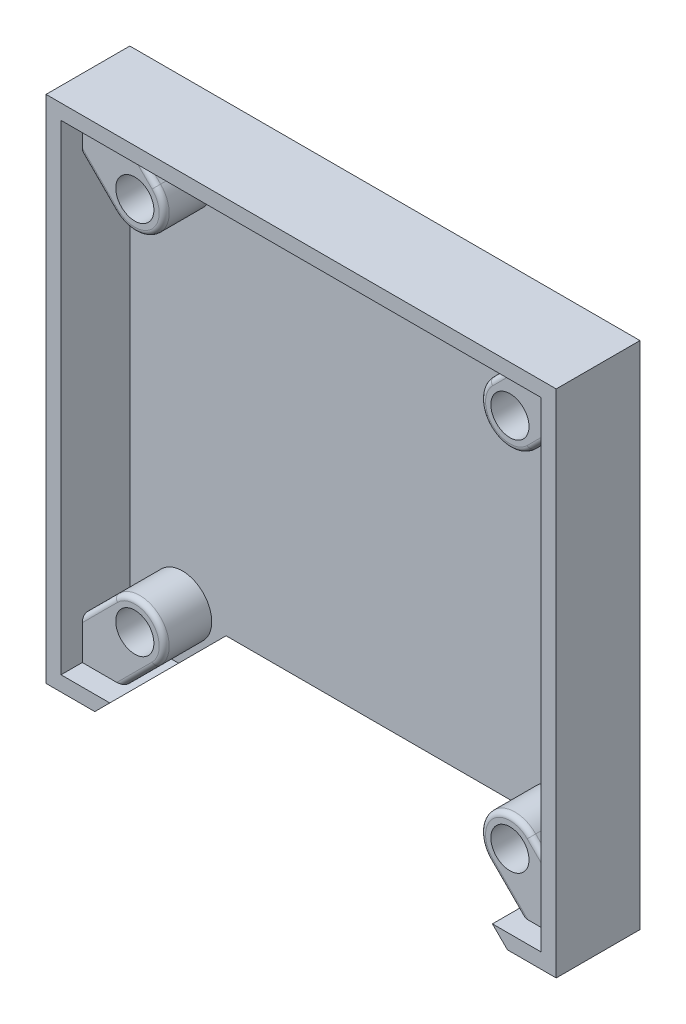
SolidWorks part; units mm, degrees
ref_plane "Front Plane" through (0, 0, 0) normal (0, 0, 1) x (1, 0, 0)
ref_plane "Top Plane" through (0, 0, 0) normal (0, 1, 0) x (1, 0, 0)
ref_plane "Right Plane" through (0, 0, 0) normal (1, 0, 0) x (0, 0, -1)
sketch "Sketch1" plane through (0, 0, 0) normal (0, 0, 1) x (1, 0, 0)
  line L0 (20.4, 20.4) -> (-20.4, 20.4)
  line L1 (19.2, 19.2) -> (-19.2, 19.2)
  line L2 (19.2, 19.2) -> (19.2, -19.2)
  line L3 (19.2, -19.2) -> (-19.2, -19.2)
  line L4 (-19.2, 19.2) -> (-19.2, -19.2)
  line L5 (19.2, 19.2) -> (-19.2, -19.2) construction
  line L6 (19.2, -19.2) -> (-19.2, 19.2) construction
  line L7 (-20.4, 20.4) -> (-20.4, -20.4)
  line L8 (20.4, -20.4) -> (-20.4, -20.4)
  line L9 (20.4, 20.4) -> (20.4, -20.4)
  point P0 (0, 0)
  point P5 (0, 0)
  dimension "D1" = 38.4
  dimension "D2" = 38.4
  dimension "D3" = 1.2
extrude "Boss-Extrude1" add sketch "Sketch1" along normal blind 1.7
sketch "Sketch2" plane through (0, 0, 0) normal (0, 0, -1) x (-1, 0, 0)
  line L1 (-16.6617, 13.3383) -> (-19.2, 15.8766)
  line L2 (-15, -15) -> (15, -15) construction
  line L3 (-15, -15) -> (-15, 15) construction
  line L4 (-15, 15) -> (15, 15) construction
  line L5 (-20.4, 20.4) -> (-20.4, -20.4)
  line L6 (-20.4, -20.4) -> (20.4, -20.4)
  line L7 (20.4, -20.4) -> (20.4, 20.4)
  line L8 (20.4, 20.4) -> (-20.4, 20.4)
  line L9 (-20.4, 20.4) -> (-20.4, -20.4)
  line L10 (-20.4, -20.4) -> (20.4, -20.4)
  line L11 (20.4, -20.4) -> (20.4, 20.4)
  line L12 (20.4, 20.4) -> (-20.4, 20.4)
  line L13 (19.2, 19.2) -> (-19.2, 19.2)
  line L14 (19.2, -19.2) -> (19.2, 19.2)
  line L15 (-19.2, -19.2) -> (19.2, -19.2)
  line L16 (-19.2, 19.2) -> (-19.2, -19.2)
  line L17 (19.2, 19.2) -> (-19.2, 19.2)
  line L18 (19.2, -19.2) -> (19.2, 19.2)
  line L19 (-19.2, -19.2) -> (19.2, -19.2)
  line L20 (-19.2, 19.2) -> (-19.2, -19.2)
  line L21 (15, -15) -> (15, 15) construction
  line L22 (-15, -15) -> (15, 15) construction
  line L23 (-15, 15) -> (15, -15) construction
  line L24 (-13.3383, 16.6617) -> (-15.8766, 19.2)
  line L25 (0, 0) -> (0, 15) construction
  line L26 (0, 0) -> (15, 0) construction
  line L27 (13.3383, 16.6617) -> (15.8766, 19.2)
  line L28 (16.6617, 13.3383) -> (19.2, 15.8766)
  line L29 (-13.3383, -16.6617) -> (-15.8766, -19.2)
  line L30 (16.6617, -13.3383) -> (19.2, -15.8766)
  line L31 (13.3383, -16.6617) -> (15.8766, -19.2)
  line L32 (-16.6617, -13.3383) -> (-19.2, -15.8766)
  circle A0 centre (-15, 15) radius 2.35
  circle A1 centre (15, 15) radius 2.35
  circle A2 centre (-15, -15) radius 2.35
  circle A3 centre (15, -15) radius 2.35
  point P4 (0, 0)
  point P29 (-14.6074, 17.9309)
  line M21 (-20.4, 20.4) -> (-20.4, -20.4)
  line M22 (-20.4, -20.4) -> (20.4, -20.4)
  line M23 (20.4, -20.4) -> (20.4, 20.4)
  line M24 (20.4, 20.4) -> (-20.4, 20.4)
  line M25 (-19.2, 19.2) -> (19.2, 19.2)
  line M26 (19.2, 19.2) -> (19.2, -19.2)
  line M27 (19.2, -19.2) -> (-19.2, -19.2)
  line M28 (-19.2, -19.2) -> (-19.2, 19.2)
  dimension "D3" = 4.7
  dimension "D4" = 30
  dimension "D5" = 30
  dimension "D1" = 0
  dimension "D2" = 0
extrude "Boss-Extrude2" add sketch "Sketch2" along normal blind 3.8 contours L20 L17 L18 L19 M24 M21 M22 M23 M28 M25 M26 M27 | A0 L24 L1 M25 M28 | A1 L28 L27 M26 M25 | A1 | A0 | A3 | A3 L31 L30 M27 M26 | A2 | A2 L32 L19 L29 M28
sketch "Sketch3" plane through (0, 0, -3.8) normal (0, 0, -1) x (-1, 0, 0)
  line L4 (20.4, 20.4) -> (-20.4, 20.4)
  line L5 (-20.4, 20.4) -> (-20.4, -20.4)
  line L6 (-20.4, -20.4) -> (20.4, -20.4)
  line L7 (20.4, -20.4) -> (20.4, 20.4)
  line L8 (20.4, 20.4) -> (-20.4, 20.4)
  line L9 (-20.4, 20.4) -> (-20.4, -20.4)
  line L10 (-20.4, -20.4) -> (20.4, -20.4)
  line L11 (20.4, -20.4) -> (20.4, 20.4)
  dimension "D1" = 0
extrude "Boss-Extrude3" add sketch "Sketch3" along normal blind 1.2
sketch "Sketch4" plane through (0, 0, -5) normal (0, 0, -1) x (-1, 0, 0)
  line L0 (-20.4, -20.4) -> (20.4, -20.4) construction
  line L1 (-11.5, -25.4) -> (11.5, -25.4)
  line L2 (-11.5, -25.4) -> (-11.5, -15.4)
  line L3 (-11.5, -15.4) -> (11.5, -15.4)
  line L4 (11.5, -25.4) -> (11.5, -15.4)
  line L5 (-11.5, -25.4) -> (11.5, -15.4) construction
  line L6 (-11.5, -15.4) -> (11.5, -25.4) construction
  point P0 (0, -20.4)
  dimension "D1" = 23
  dimension "D2" = 5
extrude "Cut-Extrude1" cut sketch "Sketch4" against normal through all
sketch "Sketch5" plane through (0, 0, -3.8) normal (0, 0, 1) x (1, 0, 0)
  line L0 (-11.5, -15.4) -> (-17.6584, -21.5584)
  line L1 (-17.6584, -21.5584) -> (17.6584, -21.5584)
  line L2 (17.6584, -21.5584) -> (11.5, -15.4)
  line L3 (11.5, -15.4) -> (-11.5, -15.4)
  line L4 (-13.3383, -16.6617) -> (-15.8766, -19.2) construction
  line L5 (13.3383, -16.6617) -> (15.8766, -19.2) construction
extrude "Cut-Extrude2" cut sketch "Sketch5" against normal through all both and the other way through all
sketch "Sketch6" plane through (0, 0, 0) normal (0, 0, 1) x (1, 0, 0)
  circle A0 centre (-15, -15) radius 1.525
  circle A1 centre (-15, 15) radius 1.525
  circle A2 centre (15, 15) radius 1.525
  circle A3 centre (15, -15) radius 1.525
  dimension "D1" = 3.05
extrude "Cut-Extrude3" cut sketch "Sketch6" against normal through all
fillet "Fillet1" radius 0.4 12 edges at (14.6074, -17.9309, 0) (17.9309, -14.6074, 0) (-17.9309, -14.6074, 0) (-14.6074, -17.9309, 0) (17.9309, 14.6074, 0) (14.6074, 17.9309, 0) (-14.6074, 17.9309, 0) (-17.9309, 14.6074, 0) (13.3383, -13.3383, 0) (-13.3383, -13.3383, 0) (13.3383, 13.3383, 0) (-13.3383, 13.3383, 0)
